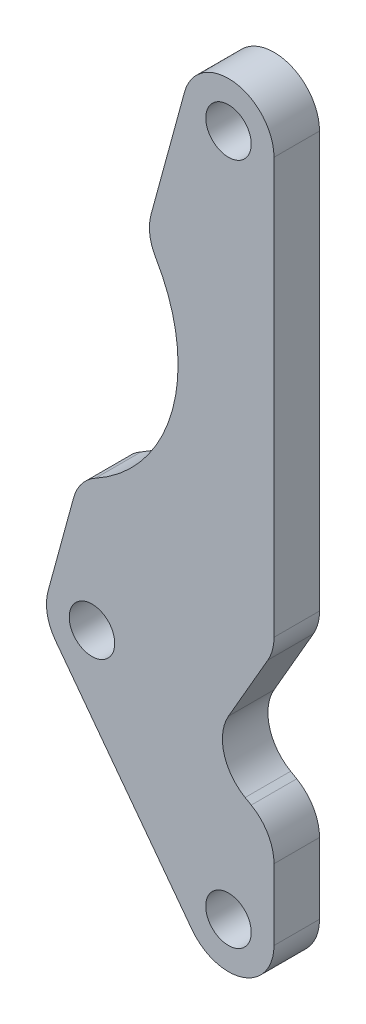
SolidWorks part; units mm, degrees
ref_plane "Front Plane" through (0, 0, 0) normal (0, 0, 1) x (1, 0, 0)
ref_plane "Top Plane" through (0, 0, 0) normal (0, 1, 0) x (1, 0, 0)
ref_plane "Right Plane" through (0, 0, 0) normal (1, 0, 0) x (0, 0, -1)
sketch "Sketch1" plane through (0, 0, 0) normal (0, 0, 1) x (1, 0, 0)
  line L0 (-15, 0) -> (-15, 5) construction
  line L1 (-15, 0) -> (0, 0) construction
  line L2 (0, 0) -> (0, -15) construction
  line L3 (0, 0) -> (0, 60) construction
  line L4 (5, 60) -> (5, -15)
  line L5 (-4.8238, 61.3156) -> (-19.8238, 6.3156)
  line L6 (-19, 2) -> (-4, -18)
  circle A0 centre (-15, 5) radius 5
  circle A1 centre (0, -15) radius 5
  circle A2 centre (0, 60) radius 5
  circle A5 centre (0, 60) radius 2.5
  circle A6 centre (-15, 5) radius 2.5
  circle A7 centre (0, -15) radius 2.5
  dimension "D1" = 10
  dimension "D2" = 10
  dimension "D5" = 10
  dimension "D8" = 5
  dimension "D3" = 15
  dimension "D4" = 15
  dimension "D6" = 60
  dimension "D7" = 5
extrude "Boss-Extrude1" add sketch "Sketch1" along normal blind 5 contours A2 L5 A0 L6 A1 L4 | A0 A6 | A1 A7 | A2 A5
sketch "Sketch3" plane through (0, 0, 5) normal (0, 0, 1) x (1, 0, 0)
  line L0 (-2.5, 0) -> (0, 0) construction
  line L1 (5, 12.9904) -> (5, -4.3301)
  line L2 (5, 60) -> (5, -15) construction
  line L3 (5, -4.3301) -> (-2.5, 0)
  line L4 (-2.5, 0) -> (5, 12.9904)
  dimension "D1" = 2.5
  dimension "D2" = 30
  dimension "D3" = 60
extrude "Cut-Extrude2" cut sketch "Sketch3" against normal blind 5
fillet "Fillet1" radius 5 3 edges at (5, -4.3301, 2.5) (5, 12.9904, 2.5) (-2.5, 0, 2.5)
sketch "Sketch4" plane through (0, 0, 5) normal (0, 0, 1) x (1, 0, 0)
  line L0 (-15, 5) -> (-23.0385, 35) construction
  line L1 (-4.8238, 61.3156) -> (-19.8238, 6.3156) construction
  line L2 (-23.0385, 35) -> (-6.1551, 30.3954) construction
  line L3 (-9.111, 45.596) -> (-16.4189, 18.8003)
  line L4 (-15, 5) -> (-15, 29.979) construction
  arc A0 (-9.111, 45.596) -> (-16.4189, 18.8003) centre (-23.0385, 35) cw
  dimension "D3" = 17.5
  dimension "D1" = 15
  dimension "D2" = 30
extrude "Cut-Extrude3" cut sketch "Sketch4" against normal through all
fillet "Fillet2" radius 5 2 edges at (-9.111, 45.596, 2.5) (-16.4189, 18.8003, 2.5)
